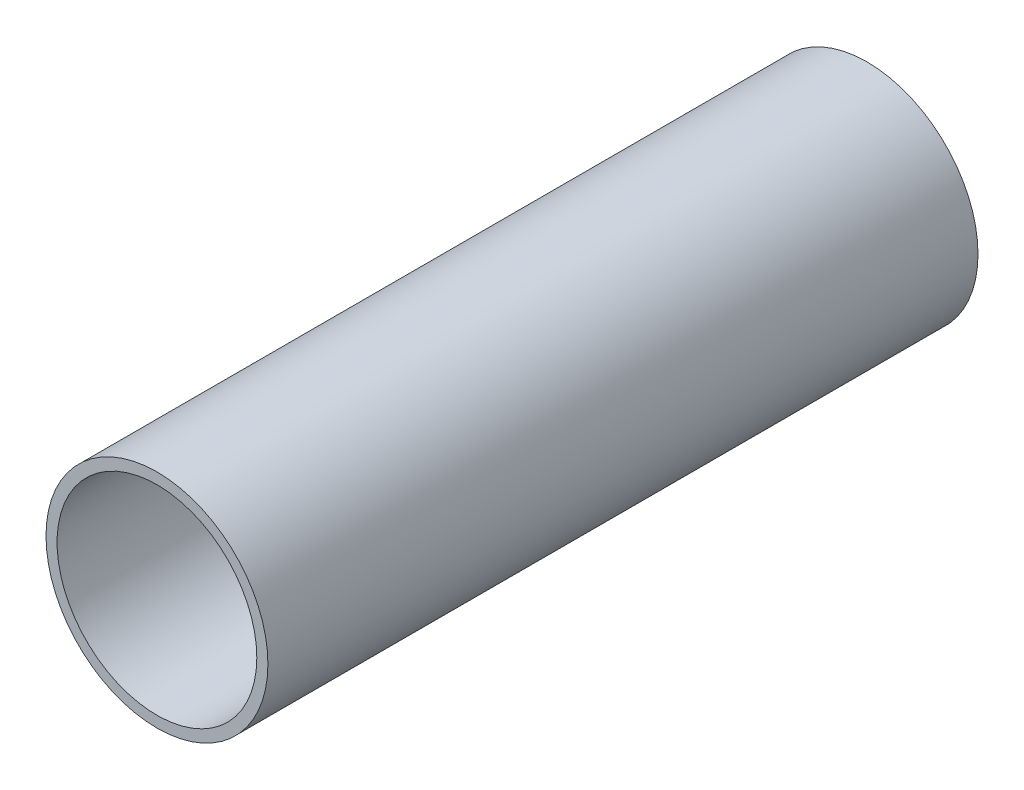
SolidWorks part; units mm, degrees
material "Thornel Mat VMA"
ref_plane "前视基准面" through (0, 0, 0) normal (0, 0, 1) x (1, 0, 0)
ref_plane "上视基准面" through (0, 0, 0) normal (0, 1, 0) x (1, 0, 0)
ref_plane "右视基准面" through (0, 0, 0) normal (1, 0, 0) x (0, 0, -1)
other "Configuration Table"
sketch "草图1" plane through (0, 0, 0) normal (0, 0, 1) x (1, 0, 0)
  circle A0 centre (0, 0) radius 10
  circle A1 centre (0, 0) radius 9
  dimension "D1" = 20
  dimension "D2" = 18
extrude "凸台-拉伸1" add sketch "草图1" along normal blind 64
